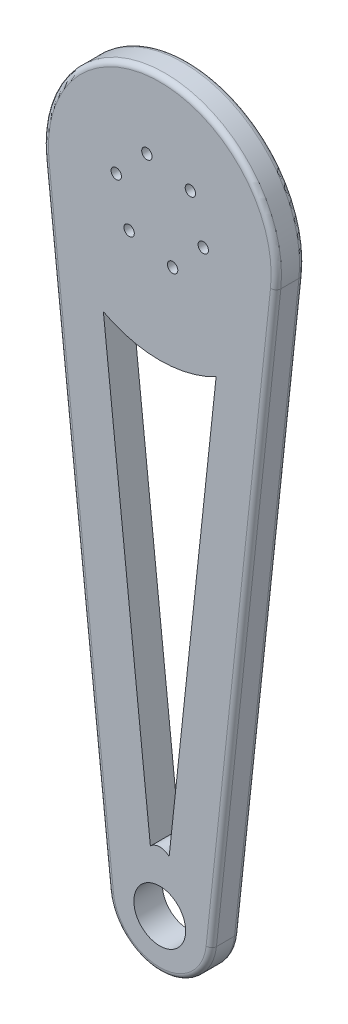
SolidWorks part; units mm, degrees
ref_plane "前视基准面" through (0, 0, 0) normal (0, 0, 1) x (1, 0, 0)
ref_plane "上视基准面" through (0, 0, 0) normal (0, 1, 0) x (1, 0, 0)
ref_plane "右视基准面" through (0, 0, 0) normal (1, 0, 0) x (0, 0, -1)
sketch "草图1" plane through (0, 0, 0) normal (0, 0, 1) x (1, 0, 0)
  line L1 (-44.7446, -4.7872) -> (-19.8865, -237.1277)
  line L2 (44.7446, -4.7872) -> (19.8865, -237.1277)
  arc A2 (-44.7446, -4.7872) -> (44.7446, -4.7872) centre (0, 0) cw
  arc A3 (-19.8865, -237.1277) -> (19.8865, -237.1277) centre (0, -235) ccw
extrude "凸台-拉伸1" add sketch "草图1" along normal blind 11
sketch "草图2" plane through (0, 0, 0) normal (0, 0, -1) x (-1, 0, 0)
  line L0 (0, 0) -> (0, -95.701) construction
  circle A0 centre (0, -235.836) radius 10
extrude "切除-拉伸1" cut sketch "草图2" against normal blind 11
fillet "圆角1" radius 2 8 edges at (0, 45, 11) (0, -255, 11) (32.3156, -120.9574, 11) (-32.3156, -120.9574, 11) (0, -255, 0) (-32.3156, -120.9574, 0) (0, 45, 0) (32.3156, -120.9574, 0)
sketch "草图3" plane through (0, 0, 11) normal (0, 0, 1) x (1, 0, 0)
  circle A0 centre (0, -235.836) radius 10
sketch "草图4" plane through (0, 0, 0) normal (0, 0, -1) x (-1, 0, 0)
  line L0 (0, 0) -> (0, -235.836) construction
  line L1 (-21.7598, -44.6823) -> (-3.626, -214.173)
  line L3 (21.7598, -44.6823) -> (3.6153, -214.2726)
  line L4 (17.8979, -236.9149) -> (42.756, -4.5745) construction
  line L5 (-42.756, -4.5745) -> (-17.8979, -236.9149) construction
  arc A2 (21.7598, -44.6823) -> (-21.7598, -44.6823) centre (0, -3.3509) cw
  arc A3 (-3.626, -214.173) -> (3.6153, -214.2726) centre (-0.0551, -217.8435) cw
  point P7 (0, -44.6823)
extrude "切除-拉伸2" cut sketch "草图4" against normal blind 20
sketch "草图6" plane through (0, 0, 11) normal (0, 0, 1) x (1, 0, 0)
  circle A0 centre (-16.7892, 3.9603) radius 2
  circle A1 centre (-4.9649, 16.52) radius 2
  circle A2 centre (11.8243, 12.5598) radius 2
  circle A3 centre (16.7892, -3.9603) radius 2
  circle A4 centre (4.9649, -16.52) radius 2
  circle A5 centre (-11.8243, -12.5598) radius 2
  point P15 (0, 0)
  dimension "D1" = 6
  dimension "D2" = 17.25
extrude "切除-拉伸4" cut sketch "草图6" against normal blind 33
